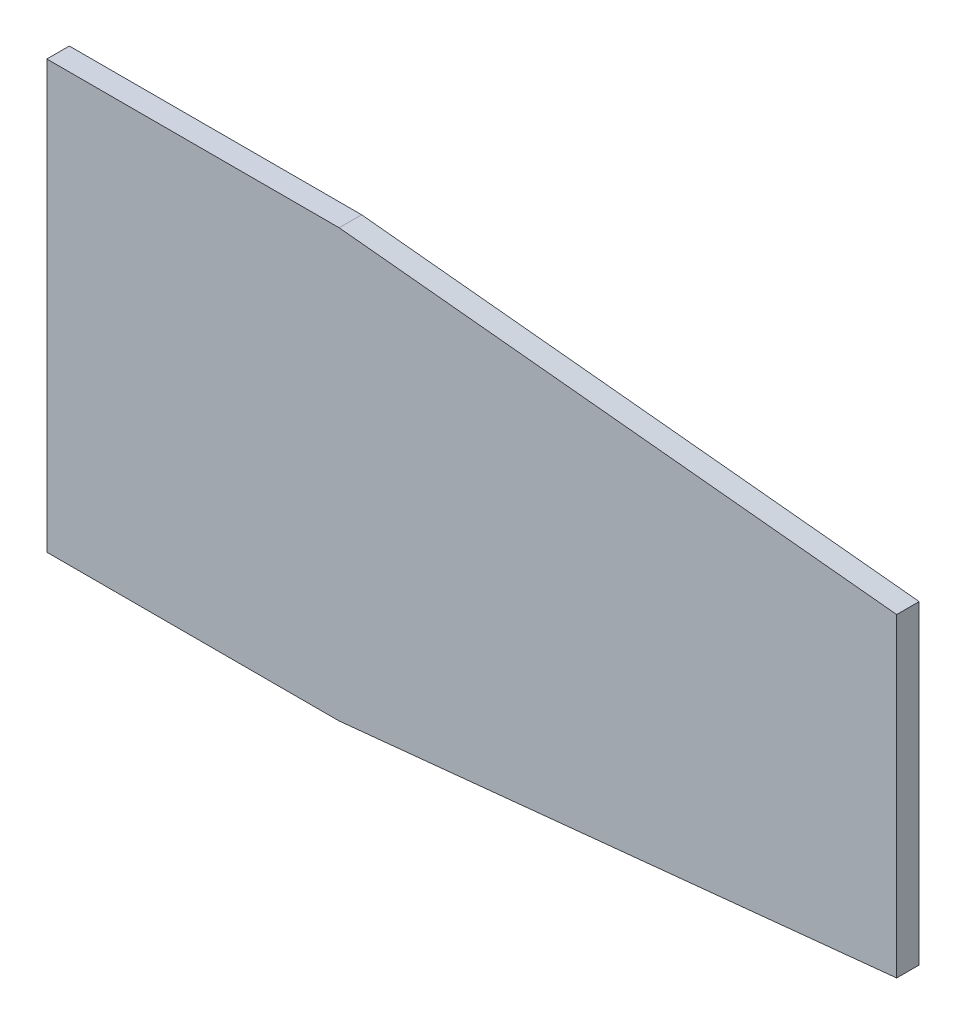
SolidWorks part; units mm, degrees
ref_plane "Ebene vorne" through (0, 0, 0) normal (0, 0, 1) x (1, 0, 0)
ref_plane "Ebene oben" through (0, 0, 0) normal (0, 1, 0) x (1, 0, 0)
ref_plane "Ebene rechts" through (0, 0, 0) normal (1, 0, 0) x (0, 0, -1)
sketch "Skizze1" plane through (0, 0, 0) normal (0, 0, 1) x (1, 0, 0)
  line L0 (0, 0) -> (189, 0) construction
  line L1 (0, -47.5) -> (0, 47.5)
  line L2 (0, 47.5) -> (65, 47.5)
  line L3 (65, 47.5) -> (189, 35)
  line L4 (189, 35) -> (189, -35)
  line L5 (65, -47.5) -> (189, -35)
  line L6 (0, -47.5) -> (65, -47.5)
  dimension "D1" = 95
  dimension "D2" = 189
  dimension "D3" = 70
  dimension "D4" = 65
extrude "Aufsatz-Linear austragen1" add sketch "Skizze1" along normal blind 5
